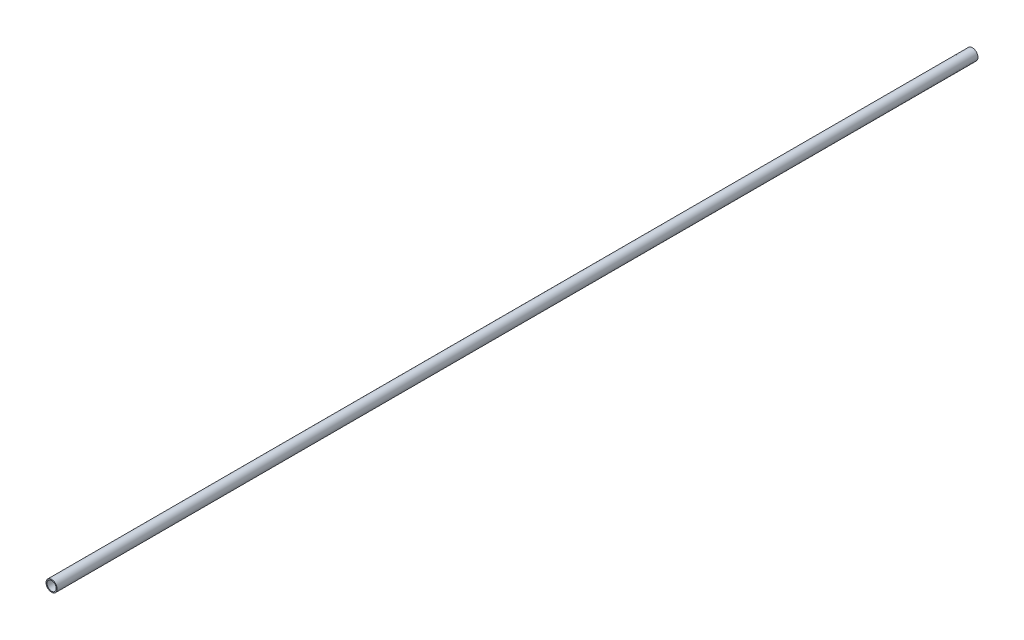
SolidWorks part; units mm, degrees
ref_plane "Front Plane" through (0, 0, 0) normal (0, 0, 1) x (1, 0, 0)
ref_plane "Top Plane" through (0, 0, 0) normal (0, 1, 0) x (1, 0, 0)
ref_plane "Right Plane" through (0, 0, 0) normal (1, 0, 0) x (0, 0, -1)
sketch "Sketch1" plane through (0, 0, 0) normal (0, 0, 1) x (1, 0, 0)
  circle A0 centre (0, 0) radius 21.082
  circle A1 centre (0, 0) radius 17.526
  dimension "D1" = 42.164
  dimension "D2" = 3.556
extrude "Boss-Extrude1" add sketch "Sketch1" along normal blind 3473.45
